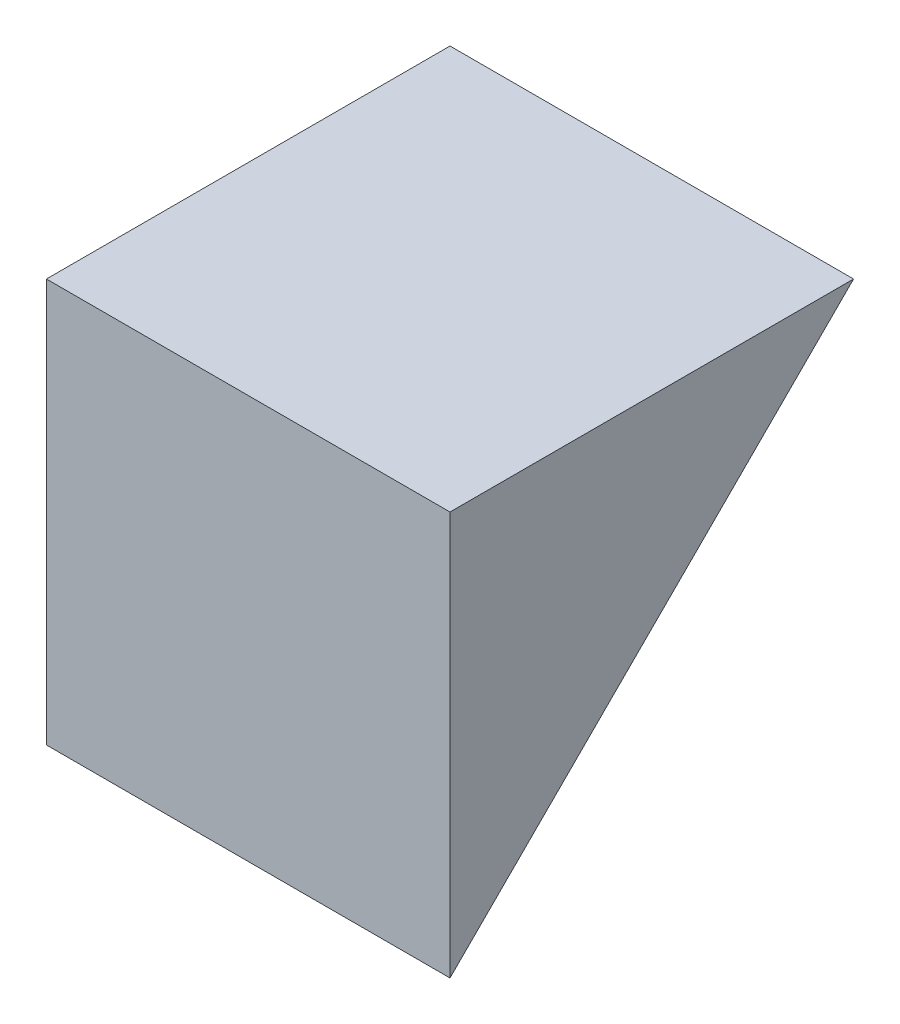
SolidWorks part; units mm, degrees
ref_plane "Přední rovina" through (0, 0, 0) normal (0, 0, 1) x (1, 0, 0)
ref_plane "Horní rovina" through (0, 0, 0) normal (0, 1, 0) x (1, 0, 0)
ref_plane "Pravá rovina" through (0, 0, 0) normal (1, 0, 0) x (0, 0, -1)
sketch "Sketch1" plane through (0, 0, 0) normal (1, 0, 0) x (0, 0, -1)
  line L0 (0, 0) -> (-40, 0)
  line L1 (-40, 0) -> (-40, -40)
  line L2 (-40, -40) -> (0, 0)
  point P3 (-40, -27.8805)
  dimension "D1" = 40
  dimension "D2" = 40
extrude "Boss-Extrude1" add sketch "Sketch1" along normal blind 40
